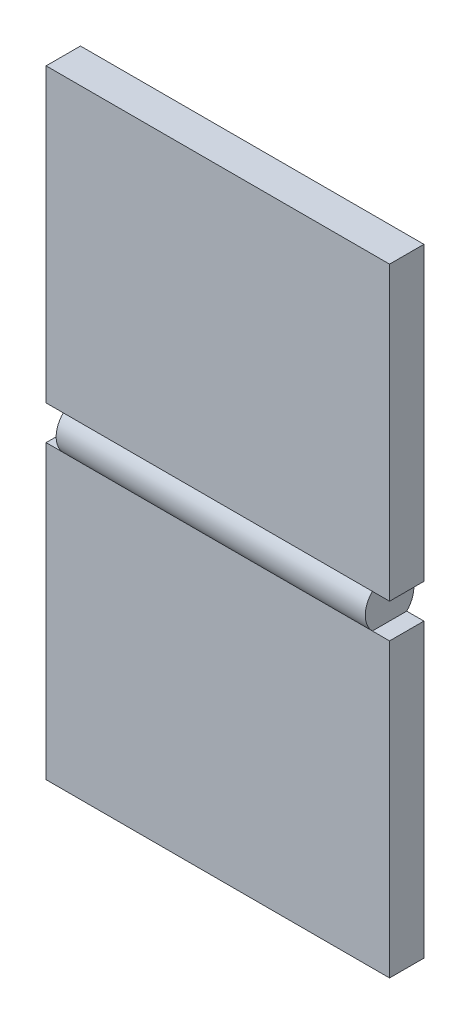
SolidWorks part; units mm, degrees
ref_plane "Front Plane" through (0, 0, 0) normal (1, 0, 0) x (0, 1, 0)
ref_plane "Top Plane" through (0, 0, 0) normal (0, 0, 1) x (0, 1, 0)
ref_plane "Right Plane" through (0, 0, 0) normal (0, 1, 0) x (-1, 0, 0)
sketch "Sketch1" plane through (0, 0, 0) normal (0, 0, 1) x (0, 1, 0)
  line L1 (-18, 10) -> (-1, 10)
  line L2 (-18, 10) -> (-18, -10)
  line L3 (-18, -10) -> (-1, -10)
  line L4 (-1, 10) -> (-1, -10)
  line L5 (1, 10) -> (18, 10)
  line L6 (1, 10) -> (1, -10)
  line L7 (1, -10) -> (18, -10)
  line L8 (18, 10) -> (18, -10)
  point P8 (-1, 0)
  point P10 (1, 0)
  point P11 (1, -10)
  point P12 (1, 10)
  dimension "D1" = 20
  dimension "D2" = 17
  dimension "D3" = 17
  dimension "D4" = 1
  dimension "D5" = 1
extrude "Boss-Extrude1" add sketch "Sketch1" along normal blind 2
sketch "Sketch2" plane through (0, 0, 0) normal (1, 0, 0) x (0, 1, 0)
  circle A0 centre (0, 1) radius 1.4142
  dimension "D1" = 1
extrude "Boss-Extrude2" add sketch "Sketch2" along normal blind 9 and the other way blind 9
